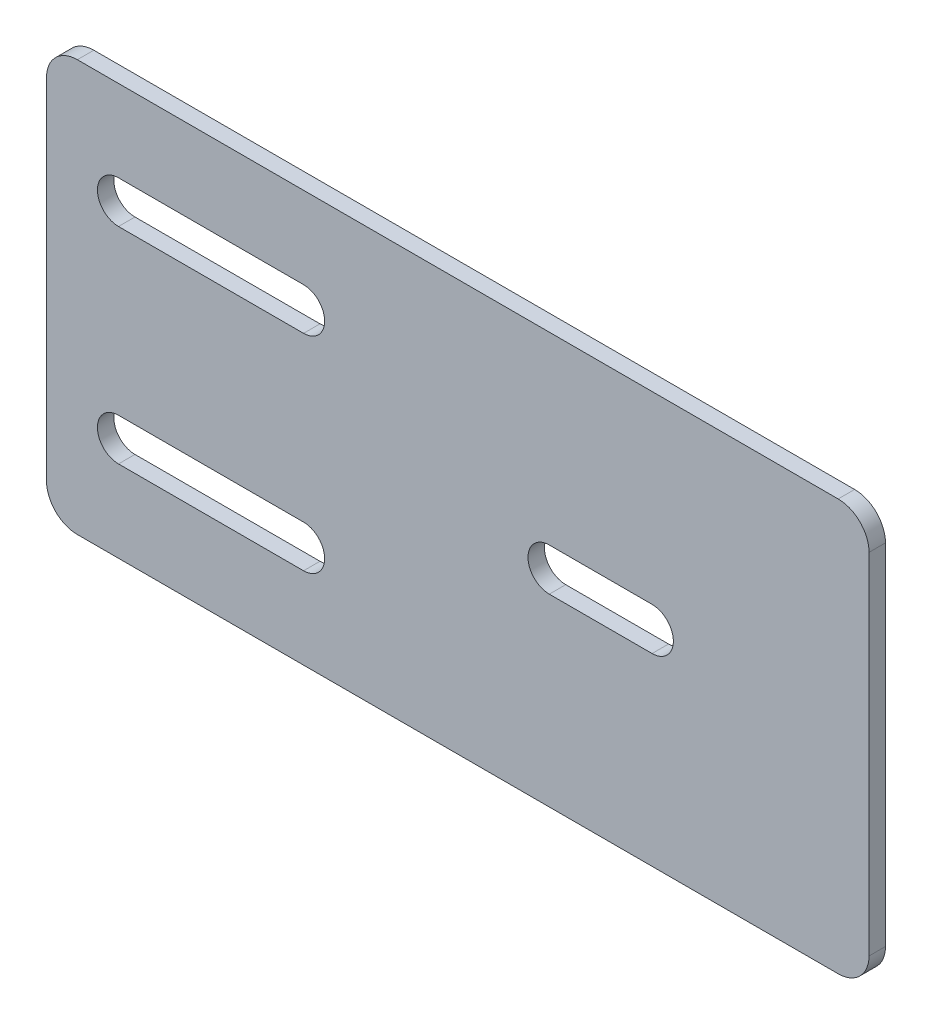
SolidWorks part; units mm, degrees
ref_plane "Front Plane" through (0, 0, 0) normal (0, 0, 1) x (1, 0, 0)
ref_plane "Top Plane" through (0, 0, 0) normal (0, 1, 0) x (1, 0, 0)
ref_plane "Right Plane" through (0, 0, 0) normal (1, 0, 0) x (0, 0, -1)
sketch "Sketch1" plane through (0, 0, 0) normal (0, 0, 1) x (1, 0, 0)
  line L0 (-15, 10) -> (-33, 10) construction
  line L1 (-40, 20) -> (40, 20)
  line L2 (-40, 20) -> (-40, -20)
  line L3 (-40, -20) -> (40, -20)
  line L4 (40, 20) -> (40, -20)
  line L5 (-40, 20) -> (40, -20) construction
  line L6 (-40, -20) -> (40, 20) construction
  line L7 (-15, 7.95) -> (-33, 7.95)
  line L8 (-15, 12.05) -> (-33, 12.05)
  line L9 (-40, 0) -> (40, 0) construction
  line L10 (-15, -10) -> (-33, -10) construction
  line L11 (-15, -7.95) -> (-33, -7.95)
  line L12 (-15, -12.05) -> (-33, -12.05)
  line L13 (8.9, 0) -> (18.9, 0) construction
  line L14 (8.9, 2.07) -> (18.9, 2.07)
  line L15 (8.9, -2.07) -> (18.9, -2.07)
  arc A0 (-15, 7.95) -> (-15, 12.05) centre (-15, 10) ccw
  arc A1 (-33, 12.05) -> (-33, 7.95) centre (-33, 10) ccw
  arc A2 (-15, -7.95) -> (-15, -12.05) centre (-15, -10) cw
  arc A3 (-33, -12.05) -> (-33, -7.95) centre (-33, -10) cw
  arc A4 (8.9, 2.07) -> (8.9, -2.07) centre (8.9, 0) ccw
  arc A5 (18.9, -2.07) -> (18.9, 2.07) centre (18.9, 0) ccw
  point P0 (0, 0)
  point P8 (-24, 10)
  point P17 (-24, -10)
  point P24 (13.9, 0)
  dimension "D3" = 2.05
  dimension "D7" = 2.07
  dimension "D1" = 40
  dimension "D2" = 80
  dimension "D4" = 18
  dimension "D5" = 10
  dimension "D6" = 55
  dimension "D8" = 10
  dimension "D9" = 21.1
extrude "Boss-Extrude1" add sketch "Sketch1" along normal blind 1.6
fillet "Fillet1" radius 3 4 edges at (40, -20, 0.8) (-40, -20, 0.8) (40, 20, 0.8) (-40, 20, 0.8)
